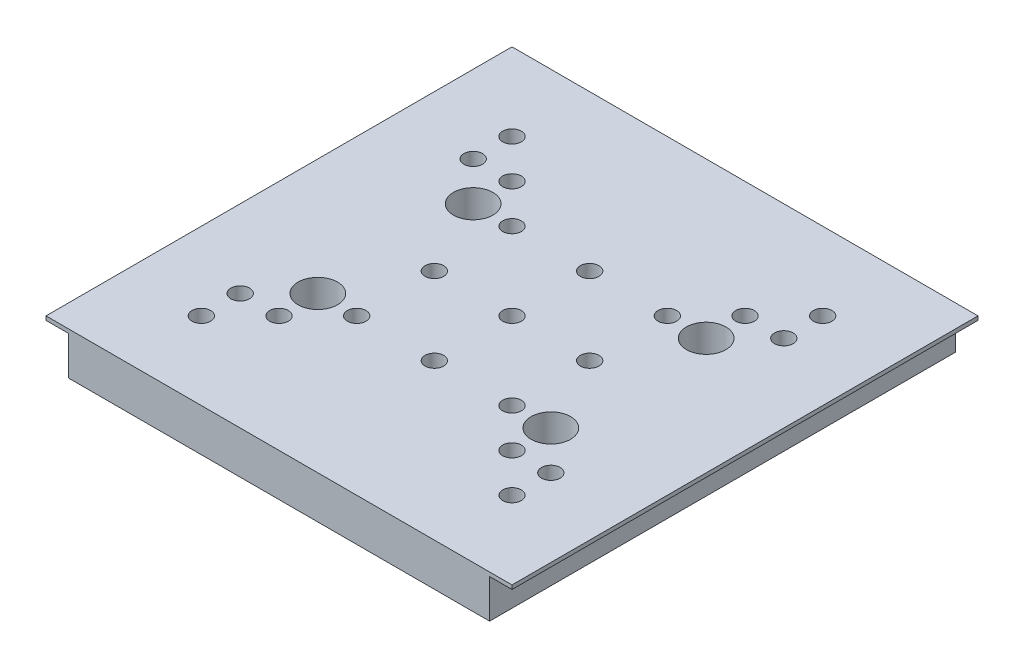
SolidWorks part; units mm, degrees
ref_plane "MIDPLANE" through (0, 0, 0) normal (0, 0, 1) x (1, 0, 0)
ref_plane "BOTTOM" through (0, 0, 0) normal (0, 1, 0) x (1, 0, 0)
ref_plane "Right" through (0, 0, 0) normal (1, 0, 0) x (0, 0, -1)
sketch "Sketch1" plane through (0, 0, 0) normal (0, 0, 1) x (1, 0, 0)
  line L0 (0, 0) -> (0, 60.4356) construction
  line L1 (-67.79, 0) -> (67.79, 0)
  line L2 (67.79, 0) -> (67.79, 12.446)
  line L3 (-67.79, 0) -> (-67.79, 12.446)
  line L4 (67.79, 12.446) -> (75, 12.446)
  line L5 (-67.79, 12.446) -> (-75, 12.446)
  line L6 (75, 12.446) -> (75, 13.716)
  line L7 (-75, 12.446) -> (-75, 13.716)
  line L8 (75, 13.716) -> (-75, 13.716)
  point P12 (0, 13.716)
  dimension "D1" = 150
  dimension "D2" = 135.58
  dimension "D3" = 13.716
  dimension "D4" = 1.27
extrude "Extrude1" add sketch "Sketch1" along normal mid plane 150
hole_wizard "1/2 (0.500000) Diameter Hole1" positions "Sketch3" profile "Sketch2" hole size "1/2" standard "Ansi Inch" end condition through all
sketch "Sketch3" plane through (0, 13.716, 0) normal (0, 1, 0) x (-1, 0, 0)
  line L0 (0, 91.1849) -> (0, -92.7414) construction
  line L1 (0, 7.5438) -> (0, -7.5438) construction
  line L2 (-94.2979, 0) -> (98.4486, 0) construction
  line L3 (7.5438, 0) -> (-7.5438, 0) construction
  point P0 (37.5, 25)
  point P1 (-37.5, 25)
  point P2 (-37.5, -25)
  point P3 (37.5, -25)
  dimension "D1" = 75
  dimension "D2" = 50
sketch "Sketch2" plane through (-37.5, 13.716, 25) normal (1, 0, 0) x (0, 0, 1)
  line L0 (0, 0) -> (0, 13.716)
  line L1 (0, 13.716) -> (6.35, 13.716)
  line L2 (6.35, 13.716) -> (6.35, 0)
  line L5 (6.35, 0) -> (0, 0)
  line L11 (0, -6.35) -> (0, 107.95) construction
  dimension "Thru Hole Dia." = 12.7
  dimension "Thru Hole Depth" = 13.716
hole_wizard "M6x1.0 Tapped Hole1" positions "Sketch5" profile "Sketch4" tap size "M6x1.0" standard "Ansi Metric" end condition through all
sketch "Sketch5" plane through (0, 13.716, 0) normal (0, 1, 0) x (-1, 0, 0)
  point P0 (0, 0)
sketch "Sketch4" plane through (0, 13.716, 0) normal (1, 0, 0) x (0, 0, 1)
  line L0 (0, 0) -> (0, 13.716)
  line L1 (0, 13.716) -> (3, 13.716)
  line L2 (3, 13.716) -> (3, 0)
  line L5 (3, 0) -> (0, 0)
  line L11 (0, -6.35) -> (0, 107.95) construction
  dimension "Thread Major Dia." = 6
  dimension "Thru Tap Drill Depth" = 13.716
pattern_linear "LPattern1" count 2 spacing 25 along (-1, 0, 0) count 2 spacing 25 along (0, 0, -1) of "M6x1.0 Tapped Hole1"
hole_wizard "M6x1.0 Tapped Hole2" positions "Sketch7" profile "Sketch6" tap size "M6x1.0" standard "Ansi Metric" end condition up to next
sketch "Sketch7" plane through (0, 13.716, 0) normal (0, 1, 0) x (-1, 0, 0)
  line L0 (7.5438, 0) -> (-7.5438, 0) construction
  line L1 (0, 7.5438) -> (0, -7.5438) construction
  point P0 (37.5, -37.5)
  point P1 (50, -37.5)
  point P2 (50, -50)
  dimension "D1" = 37.5
  dimension "D2" = 50
  dimension "D3" = 37.5
  dimension "D4" = 50
sketch "Sketch6" plane through (-37.5, 13.716, -37.5) normal (1, 0, 0) x (0, 0, 1)
  line L0 (0, 0) -> (0, 13.717)
  line L1 (0, 13.717) -> (3, 13.717)
  line L2 (3, 13.717) -> (3, 0)
  line L5 (3, 0) -> (0, 0)
  line L11 (0, -6.35) -> (0, 107.95) construction
  dimension "Thread Major Dia." = 6
  dimension "Thru Tap Drill Depth" = 13.717
mirror "Mirror2" about plane through (0, 0, 0) normal (0, 0, 1) of "M6x1.0 Tapped Hole2", "LPattern1"
mirror "Mirror3" about plane through (0, 0, 0) normal (1, 0, 0) of "Mirror2", "M6x1.0 Tapped Hole2", "LPattern1"
hole_wizard "1/4-20 Tapped Hole1" [suppressed] positions "Sketch9" profile "Sketch8" tap size "1/4-20" standard "Ansi Inch"
sketch "Sketch9" plane through (0, 13.716, 0) normal (0, 1, 0) x (-1, 0, 0)
  point P0 (0, 0)
sketch "Sketch8" plane through (0, 13.716, 0) normal (1, 0, 0) x (0, 0, 1)
  line L0 (0, 0) -> (0, 13.716)
  line L1 (0, 13.716) -> (3.175, 13.716)
  line L2 (3.175, 13.716) -> (3.175, 0)
  line L5 (3.175, 0) -> (0, 0)
  line L11 (0, -6.35) -> (0, 107.95) construction
  dimension "Thread Major Dia." = 6.35
  dimension "Thru Tap Drill Depth" = 13.716
pattern_linear "LPattern2" [suppressed] count 2 spacing 25.4 count 2 spacing 25.4
hole_wizard "1/4-20 Tapped Hole2" [suppressed] positions "Sketch11" profile "Sketch10" tap size "1/4-20" standard "Ansi Inch"
sketch "Sketch11" plane through (0, 13.716, 0) normal (0, 1, 0) x (-1, 0, 0)
  line L0 (7.5438, 0) -> (-7.5438, 0) construction
  line L1 (0, 7.5438) -> (0, -7.5438) construction
  point P0 (38.1, -38.1)
  point P1 (50.8, -38.1)
  point P2 (50.8, -50.8)
  dimension "D1" = 38.1
  dimension "D2" = 50.8
  dimension "D3" = 38.1
  dimension "D4" = 50.8
sketch "Sketch10" plane through (-38.1, 13.716, -38.1) normal (1, 0, 0) x (0, 0, 1)
  line L0 (0, 0) -> (0, 13.717)
  line L1 (0, 13.717) -> (3.175, 13.717)
  line L2 (3.175, 13.717) -> (3.175, 0)
  line L5 (3.175, 0) -> (0, 0)
  line L11 (0, -6.35) -> (0, 107.95) construction
  dimension "Thread Major Dia." = 6.35
  dimension "Thru Tap Drill Depth" = 13.717
mirror "Mirror4" [suppressed] about plane through (0, 0, 0) normal (0, 0, 1)
mirror "Mirror5" [suppressed] about plane through (0, 0, 0) normal (1, 0, 0)
